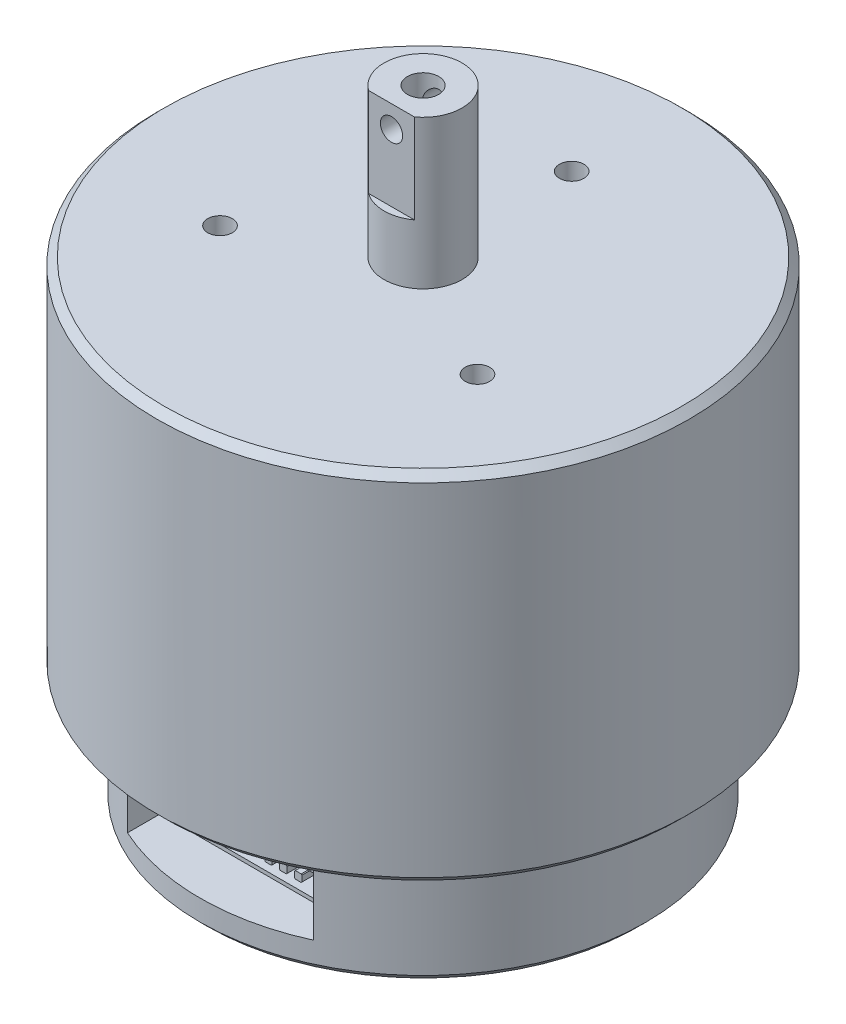
SolidWorks part; units mm, degrees
ref_plane "前视基准面" through (0, 0, 0) normal (0, 0, 1) x (1, 0, 0)
ref_plane "上视基准面" through (0, 0, 0) normal (0, 1, 0) x (1, 0, 0)
ref_plane "右视基准面" through (0, 0, 0) normal (1, 0, 0) x (0, 0, -1)
sketch "草图1" plane through (0, 0, 0) normal (0, 0, 1) x (1, 0, 0)
  line L0 (0, 0) -> (0, 50.6166) construction
  line L1 (0, 86.6973) -> (5.25, 86.6973)
  line L2 (5.25, 86.6973) -> (5.25, 66.6973)
  line L3 (5.25, 66.6973) -> (35.8, 66.6973)
  line L4 (35.8, 66.6973) -> (35.8, 18.6973)
  line L5 (35.8, 18.6973) -> (30, 18.6973)
  line L6 (30, 18.6973) -> (30, 3.1973)
  line L7 (30, 3.1973) -> (0, 3.1973)
  line L8 (0, 86.6973) -> (0, 3.1973)
  dimension "D1" = 5.25
  dimension "D2" = 20
  dimension "D3" = 83.5
  dimension "D4" = 35.8
  dimension "D5" = 30
  dimension "D6" = 48
revolve "旋转1" add sketch "草图1" angle 360 about L0
hole_wizard "M5 螺纹孔1" positions "3D草图1" profile "草图2" tap size "M5" standard "IS"
sketch3d "3D草图1"
  line L0 (0, 86.6973, 0) -> (0, 66.6973, 0) construction
  point P0 (0, 86.6973, 0)
sketch "草图2" plane through (0, 86.6973, 0) normal (1, 0, 0) x (0, 0, 1)
  line L0 (0, 0) -> (0, 13.6618)
  line L1 (0, 13.6618) -> (2.1, 12.4)
  line L2 (2.1, 12.4) -> (2.1, 0)
  line L5 (2.1, 0) -> (0, 0)
  line L10 (0, 13.6618) -> (-2.1, 12.4) construction
  line L11 (0, -6.35) -> (0, 107.95) construction
  dimension "螺纹孔钻头直径" = 4.2
  dimension "螺纹孔钻头深度" = 12.4
  dimension "导头角度" = 118
cosmetic thread "孔螺蚊线1" parameters "D1"=10, "D2"=5
sketch "草图3" plane through (0, 86.6973, 0) normal (0, 1, 0) x (1, 0, 0)
  line L0 (0, 0) -> (0, -6.6361) construction
  line L1 (-3.0822, -4.25) -> (3.0822, -4.25)
  line L2 (3.0822, -4.25) -> (3.0822, -5.6652)
  line L3 (3.0822, -5.6652) -> (-3.0822, -5.4596)
  line L4 (-3.0822, -5.4596) -> (-3.0822, -4.25)
  circle A0 centre (0, 0) radius 5.25 construction
  point P3 (0, -4.25)
  dimension "D1" = 4.25
extrude "切除-拉伸1" cut sketch "草图3" against normal blind 12
sketch "草图4" plane through (0, 0, 4.25) normal (0, 0, 1) x (1, 0, 0)
  line L0 (0, 74.6973) -> (0, 86.6973) construction
  line L1 (3.0822, 74.6973) -> (-3.0822, 74.6973) construction
  line L2 (3.0822, 86.6973) -> (-3.0822, 86.6973) construction
  circle A0 centre (0, 83.6973) radius 1.5
  point P6 (0, 83.6973)
  point P7 (0, 83.6973)
  dimension "D2" = 3
  dimension "D1" = 9
extrude "切除-拉伸2" cut sketch "草图4" against normal blind 12
ref_plane "基准面1" through (0, 0, 35.8) normal (0, 0, 1) x (1, 0, 0)
sketch "草图5" plane through (0, 0, 35.8) normal (0, 0, 1) x (1, 0, 0)
  line L0 (0, 3.1973) -> (0, 86.6973) construction
  line L1 (-30, 3.1973) -> (30, 3.1973) construction
  line L2 (3.0822, 86.6973) -> (-3.0822, 86.6973) construction
  line L3 (-12.5, 6.9973) -> (12.5, 6.9973)
  line L4 (12.5, 6.9973) -> (12.5, 18.6973)
  line L5 (-30, 18.6973) -> (30, 18.6973) construction
  line L6 (12.5, 18.6973) -> (-12.5, 18.6973)
  line L7 (-12.5, 6.9973) -> (-12.5, 18.6973)
  point P13 (0, 18.6973)
  point P14 (0, 6.9973)
  dimension "D1" = 3.8
  dimension "D2" = 12.5
extrude "切除-拉伸3" cut sketch "草图5" against normal blind 17
sketch "草图6" plane through (0, 0, 18.8) normal (0, 0, 1) x (1, 0, 0)
  line L0 (12.5, 12.8473) -> (-12.5, 12.8473) construction
  line L1 (12.5, 6.9973) -> (12.5, 18.6973) construction
  line L2 (-12.5, 18.6973) -> (-12.5, 6.9973) construction
  line L3 (0, 12.8473) -> (0, 6.9973) construction
  line L4 (-12.5, 6.9973) -> (12.5, 6.9973) construction
  line L5 (-9.5, 11.4223) -> (9.5, 11.4223)
  line L6 (-10, 11.9223) -> (10, 11.9223)
  line L7 (-10, 11.9223) -> (-10, 7.9223)
  line L8 (-10, 7.9223) -> (10, 7.9223)
  line L9 (10, 11.9223) -> (10, 7.9223)
  line L10 (-10, 11.9223) -> (10, 7.9223) construction
  line L11 (-10, 7.9223) -> (10, 11.9223) construction
  line L12 (9.5, 11.4223) -> (9.5, 8.4223)
  line L13 (-9.5, 8.4223) -> (9.5, 8.4223)
  line L14 (-9.5, 11.4223) -> (-9.5, 8.4223)
  line L15 (0, 9.9223) -> (9.5, 9.9223) construction
  line L16 (0.5, 10.3223) -> (0.6, 10.4223)
  line L17 (0.6, 10.4223) -> (1.4, 10.4223)
  line L18 (0.5, 10.3223) -> (0.5, 9.5223)
  line L19 (0.6, 9.4223) -> (1.4, 9.4223)
  line L20 (1.5, 10.3223) -> (1.5, 9.5223)
  line L21 (0.5, 10.4223) -> (1.5, 9.4223) construction
  line L22 (0.5, 9.4223) -> (1.5, 10.4223) construction
  line L23 (0.5, 9.5223) -> (0.6, 9.4223)
  line L24 (1.4, 9.4223) -> (1.5, 9.5223)
  line L25 (1.4, 10.4223) -> (1.5, 10.3223)
  line L26 (2.6, 10.4223) -> (3.4, 10.4223)
  line L27 (2.5, 10.3223) -> (2.6, 10.4223)
  line L28 (2.5, 10.3223) -> (2.5, 9.5223)
  line L29 (2.5, 9.5223) -> (2.6, 9.4223)
  line L30 (2.6, 9.4223) -> (3.4, 9.4223)
  line L31 (3.4, 9.4223) -> (3.5, 9.5223)
  line L32 (3.5, 10.3223) -> (3.5, 9.5223)
  line L33 (3.4, 10.4223) -> (3.5, 10.3223)
  line L34 (4.6, 10.4223) -> (5.4, 10.4223)
  line L35 (4.5, 10.3223) -> (4.6, 10.4223)
  line L36 (4.5, 10.3223) -> (4.5, 9.5223)
  line L37 (4.5, 9.5223) -> (4.6, 9.4223)
  line L38 (4.6, 9.4223) -> (5.4, 9.4223)
  line L39 (5.4, 9.4223) -> (5.5, 9.5223)
  line L40 (5.5, 10.3223) -> (5.5, 9.5223)
  line L41 (5.4, 10.4223) -> (5.5, 10.3223)
  line L42 (6.6, 10.4223) -> (7.4, 10.4223)
  line L43 (6.5, 10.3223) -> (6.6, 10.4223)
  line L44 (6.5, 10.3223) -> (6.5, 9.5223)
  line L45 (6.5, 9.5223) -> (6.6, 9.4223)
  line L46 (6.6, 9.4223) -> (7.4, 9.4223)
  line L47 (7.4, 9.4223) -> (7.5, 9.5223)
  line L48 (7.5, 10.3223) -> (7.5, 9.5223)
  line L49 (7.4, 10.4223) -> (7.5, 10.3223)
  line L50 (-0.5, 9.4223) -> (-1.5, 10.4223) construction
  line L51 (-0.5, 10.4223) -> (-1.5, 9.4223) construction
  line L52 (-7.4, 10.4223) -> (-7.5, 10.3223)
  line L53 (-7.5, 10.3223) -> (-7.5, 9.5223)
  line L54 (-7.4, 9.4223) -> (-7.5, 9.5223)
  line L55 (-6.6, 9.4223) -> (-7.4, 9.4223)
  line L56 (-6.5, 9.5223) -> (-6.6, 9.4223)
  line L57 (-6.5, 10.3223) -> (-6.5, 9.5223)
  line L58 (-6.5, 10.3223) -> (-6.6, 10.4223)
  line L59 (-6.6, 10.4223) -> (-7.4, 10.4223)
  line L60 (-5.4, 10.4223) -> (-5.5, 10.3223)
  line L61 (-5.5, 10.3223) -> (-5.5, 9.5223)
  line L62 (-5.4, 9.4223) -> (-5.5, 9.5223)
  line L63 (-4.6, 9.4223) -> (-5.4, 9.4223)
  line L64 (-4.5, 9.5223) -> (-4.6, 9.4223)
  line L65 (-4.5, 10.3223) -> (-4.5, 9.5223)
  line L66 (-4.5, 10.3223) -> (-4.6, 10.4223)
  line L67 (-4.6, 10.4223) -> (-5.4, 10.4223)
  line L68 (-3.4, 10.4223) -> (-3.5, 10.3223)
  line L69 (-3.5, 10.3223) -> (-3.5, 9.5223)
  line L70 (-3.4, 9.4223) -> (-3.5, 9.5223)
  line L71 (-2.6, 9.4223) -> (-3.4, 9.4223)
  line L72 (-2.5, 9.5223) -> (-2.6, 9.4223)
  line L73 (-2.5, 10.3223) -> (-2.5, 9.5223)
  line L74 (-2.5, 10.3223) -> (-2.6, 10.4223)
  line L75 (-2.6, 10.4223) -> (-3.4, 10.4223)
  line L76 (-1.4, 10.4223) -> (-1.5, 10.3223)
  line L77 (-1.4, 9.4223) -> (-1.5, 9.5223)
  line L78 (-0.5, 9.5223) -> (-0.6, 9.4223)
  line L79 (-1.5, 10.3223) -> (-1.5, 9.5223)
  line L80 (-0.6, 9.4223) -> (-1.4, 9.4223)
  line L81 (-0.5, 10.3223) -> (-0.5, 9.5223)
  line L82 (-0.6, 10.4223) -> (-1.4, 10.4223)
  line L83 (-0.5, 10.3223) -> (-0.6, 10.4223)
  line L84 (-0.5, 15.2723) -> (-1.5, 16.2723) construction
  line L85 (-0.5, 16.2723) -> (-1.5, 15.2723) construction
  line L86 (0.5, 16.2723) -> (1.5, 15.2723) construction
  line L87 (0.5, 15.2723) -> (1.5, 16.2723) construction
  line L88 (0, 15.7723) -> (9.5, 15.7723) construction
  line L89 (-10, 17.7723) -> (10, 13.7723) construction
  line L90 (-10, 13.7723) -> (10, 17.7723) construction
  line L91 (-0.5, 15.3723) -> (-0.6, 15.2723)
  line L92 (-0.6, 15.2723) -> (-1.4, 15.2723)
  line L93 (-0.5, 15.3723) -> (-0.5, 16.1723)
  line L94 (-0.6, 16.2723) -> (-1.4, 16.2723)
  line L95 (-1.5, 15.3723) -> (-1.5, 16.1723)
  line L96 (-0.5, 16.1723) -> (-0.6, 16.2723)
  line L97 (-1.4, 16.2723) -> (-1.5, 16.1723)
  line L98 (-1.4, 15.2723) -> (-1.5, 15.3723)
  line L99 (-2.6, 15.2723) -> (-3.4, 15.2723)
  line L100 (-2.5, 15.3723) -> (-2.6, 15.2723)
  line L101 (-2.5, 15.3723) -> (-2.5, 16.1723)
  line L102 (-2.5, 16.1723) -> (-2.6, 16.2723)
  line L103 (-2.6, 16.2723) -> (-3.4, 16.2723)
  line L104 (-3.4, 16.2723) -> (-3.5, 16.1723)
  line L105 (-3.5, 15.3723) -> (-3.5, 16.1723)
  line L106 (-3.4, 15.2723) -> (-3.5, 15.3723)
  line L107 (-4.6, 15.2723) -> (-5.4, 15.2723)
  line L108 (-4.5, 15.3723) -> (-4.6, 15.2723)
  line L109 (-4.5, 15.3723) -> (-4.5, 16.1723)
  line L110 (-4.5, 16.1723) -> (-4.6, 16.2723)
  line L111 (-4.6, 16.2723) -> (-5.4, 16.2723)
  line L112 (-5.4, 16.2723) -> (-5.5, 16.1723)
  line L113 (-5.5, 15.3723) -> (-5.5, 16.1723)
  line L114 (-5.4, 15.2723) -> (-5.5, 15.3723)
  line L115 (-6.6, 15.2723) -> (-7.4, 15.2723)
  line L116 (-6.5, 15.3723) -> (-6.6, 15.2723)
  line L117 (-6.5, 15.3723) -> (-6.5, 16.1723)
  line L118 (-6.5, 16.1723) -> (-6.6, 16.2723)
  line L119 (-6.6, 16.2723) -> (-7.4, 16.2723)
  line L120 (-7.4, 16.2723) -> (-7.5, 16.1723)
  line L121 (-7.5, 15.3723) -> (-7.5, 16.1723)
  line L122 (-7.4, 15.2723) -> (-7.5, 15.3723)
  line L123 (7.4, 15.2723) -> (7.5, 15.3723)
  line L124 (7.5, 15.3723) -> (7.5, 16.1723)
  line L125 (7.4, 16.2723) -> (7.5, 16.1723)
  line L126 (6.6, 16.2723) -> (7.4, 16.2723)
  line L127 (6.5, 16.1723) -> (6.6, 16.2723)
  line L128 (6.5, 15.3723) -> (6.5, 16.1723)
  line L129 (6.5, 15.3723) -> (6.6, 15.2723)
  line L130 (6.6, 15.2723) -> (7.4, 15.2723)
  line L131 (5.4, 15.2723) -> (5.5, 15.3723)
  line L132 (5.5, 15.3723) -> (5.5, 16.1723)
  line L133 (5.4, 16.2723) -> (5.5, 16.1723)
  line L134 (4.6, 16.2723) -> (5.4, 16.2723)
  line L135 (4.5, 16.1723) -> (4.6, 16.2723)
  line L136 (4.5, 15.3723) -> (4.5, 16.1723)
  line L137 (4.5, 15.3723) -> (4.6, 15.2723)
  line L138 (4.6, 15.2723) -> (5.4, 15.2723)
  line L139 (3.4, 15.2723) -> (3.5, 15.3723)
  line L140 (3.5, 15.3723) -> (3.5, 16.1723)
  line L141 (3.4, 16.2723) -> (3.5, 16.1723)
  line L142 (2.6, 16.2723) -> (3.4, 16.2723)
  line L143 (2.5, 16.1723) -> (2.6, 16.2723)
  line L144 (2.5, 15.3723) -> (2.5, 16.1723)
  line L145 (2.5, 15.3723) -> (2.6, 15.2723)
  line L146 (2.6, 15.2723) -> (3.4, 15.2723)
  line L147 (1.4, 15.2723) -> (1.5, 15.3723)
  line L148 (1.4, 16.2723) -> (1.5, 16.1723)
  line L149 (0.5, 16.1723) -> (0.6, 16.2723)
  line L150 (1.5, 15.3723) -> (1.5, 16.1723)
  line L151 (0.6, 16.2723) -> (1.4, 16.2723)
  line L152 (0.5, 15.3723) -> (0.5, 16.1723)
  line L153 (0.6, 15.2723) -> (1.4, 15.2723)
  line L154 (0.5, 15.3723) -> (0.6, 15.2723)
  line L155 (-9.5, 14.2723) -> (-9.5, 17.2723)
  line L156 (-9.5, 17.2723) -> (9.5, 17.2723)
  line L157 (9.5, 14.2723) -> (9.5, 17.2723)
  line L158 (10, 13.7723) -> (10, 17.7723)
  line L159 (-10, 17.7723) -> (10, 17.7723)
  line L160 (-10, 13.7723) -> (-10, 17.7723)
  line L161 (-10, 13.7723) -> (10, 13.7723)
  line L162 (-9.5, 14.2723) -> (9.5, 14.2723)
  point P10 (0, 9.9223)
  point P21 (1, 9.9223)
  point P94 (-1, 9.9223)
  point P173 (-1, 15.7723)
  point P174 (1, 15.7723)
  dimension "D1" = 4
  dimension "D2" = 20
  dimension "D4" = 1
  dimension "D5" = 1
  dimension "D6" = 1
  dimension "D3" = 0.5
  dimension "D7" = 4
extrude "凸台-拉伸1" add sketch "草图6" along normal blind 5 contours L9 L6 L7 L8 L14 L5 L12 L13 | L58 L59 L52 L53 L54 L55 L56 L57 | L66 L67 L60 L61 L62 L63 L64 L65 | L74 L75 L68 L69 L70 L71 L72 L73 | L81 L83 L82 L76 L79 L77 L80 L78 | L25 L17 L16 L18 L23 L19 L24 L20 | L33 L26 L27 L28 L29 L30 L31 L32 | L41 L34 L35 L36 L37 L38 L39 L40 | L49 L42 L43 L44 L45 L46 L47 L48 | L160 L161 L158 L159 L162 L155 L156 L157 | L129 L130 L123 L124 L125 L126 L127 L128 | L137 L138 L131 L132 L133 L134 L135 L136 | L145 L146 L139 L140 L141 L142 L143 L144 | L152 L154 L153 L147 L150 L148 L151 L149 | L98 L92 L91 L93 L96 L94 L97 L95 | L106 L99 L100 L101 L102 L103 L104 L105 | L114 L107 L108 L109 L110 L111 L112 L113 | L122 L115 L116 L117 L118 L119 L120 L121
sketch "草图7" plane through (0, 0, 18.8) normal (0, 0, 1) x (1, 0, 0)
  line L0 (-12.5, 12.8473) -> (12.5, 12.8473) construction
  line L1 (-12.5, 18.6973) -> (-12.5, 6.9973) construction
  line L2 (12.5, 6.9973) -> (12.5, 18.6973) construction
  line L3 (-12.5, 13.3496) -> (12.5, 13.3496)
  line L4 (-12.5, 13.3496) -> (-12.5, 12.3496)
  line L5 (12.5, 13.3496) -> (12.5, 12.3496)
  line L6 (-12.5, 12.3496) -> (12.5, 12.3496)
  line L7 (-12.5, 13.3496) -> (12.5, 12.3496) construction
  line L8 (12.5, 13.3496) -> (-12.5, 12.3496) construction
  point P7 (0, 12.8496)
  dimension "D1" = 1
extrude "凸台-拉伸2" add sketch "草图7" along normal blind 6
sketch "草图8" plane through (0, 66.6973, 0) normal (0, 1, 0) x (1, 0, 0)
  circle A0 centre (0, 0) radius 20 construction
  point P3 (0, 20)
  dimension "D1" = 40
hole_wizard "M4 螺纹孔1" positions "3D草图2" profile "草图9" tap size "M4" standard "IS"
sketch3d "3D草图2"
  point P0 (0, 66.6973, -20)
sketch "草图9" plane through (0, 66.6973, -20) normal (1, 0, 0) x (0, 0, 1)
  line L0 (0, 0) -> (0, 8.0914)
  line L1 (0, 8.0914) -> (1.65, 7.1)
  line L2 (1.65, 7.1) -> (1.65, 0)
  line L5 (1.65, 0) -> (0, 0)
  line L10 (0, 8.0914) -> (-1.65, 7.1) construction
  line L11 (0, -6.35) -> (0, 107.95) construction
  dimension "螺纹孔钻头直径" = 3.3
  dimension "螺纹孔钻头深度" = 7.1
  dimension "导头角度" = 118
cosmetic thread "孔螺蚊线2" parameters "D1"=5, "D2"=4
pattern_circular "阵列(圆周)1" count 3 every 120 about axis through (0, 0, 0) along (0, 1, 0) of "M4 螺纹孔1"
chamfer "倒角1" distance 1 angle 45 2 edges at (0, 18.6973, -35.8) (0, 66.6973, -35.8)
chamfer "倒角2" distance 1 angle 45 1 edges at (0, 3.1973, -30)
